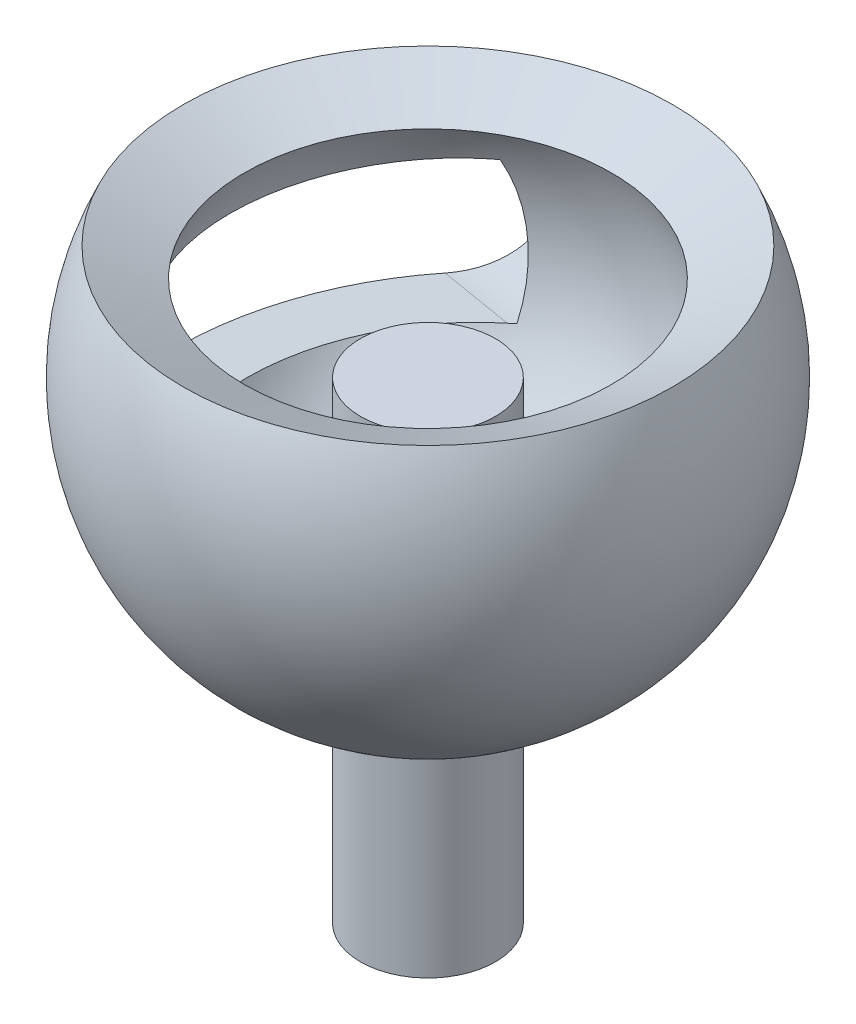
SolidWorks part; units mm, degrees
ref_plane "Plan de face" through (0, 0, 0) normal (0, 0, 1) x (1, 0, 0)
ref_plane "Plan de dessus" through (0, 0, 0) normal (0, 1, 0) x (1, 0, 0)
ref_plane "Plan de droite" through (0, 0, 0) normal (1, 0, 0) x (0, 0, -1)
sketch "Esquisse1" plane through (0, 0, 0) normal (0, 0, 1) x (1, 0, 0)
  line L0 (0, 0) -> (0, -12.9952) construction
  line L1 (0, 0) -> (0, -17.2806) construction
  line L2 (0, 0) -> (-10.8757, 5.0714) construction
  line L3 (-7.2505, 3.3809) -> (-5.4378, 2.5357)
  line L4 (0, 0) -> (10.4471, 0) construction
  line L5 (0, -6) -> (0, -8)
  arc A0 (-5.4378, 2.5357) -> (0, -6) centre (0, 0) ccw
  arc A1 (-7.2505, 3.3809) -> (0, -8) centre (0, 0) ccw
  dimension "D1" = 6
  dimension "D2" = 8
  dimension "D3" = 155
revolve "Révolution1" add sketch "Esquisse1" angle 360 about L0
sketch "Esquisse2" plane through (0, 0, 0) normal (0, 1, 0) x (1, 0, 0)
  circle A0 centre (0, 0) radius 2
  dimension "D1" = 4
extrude "Boss.-Extru.1" add sketch "Esquisse2" against normal blind 14
ref_plane "Plan1" through (-10.3936, -1.2992, -2.8186) normal (-0.9582, -0.1198, -0.2598) x (-0.2578, -0.0322, 0.9656)
sketch "Esquisse3" plane through (-10.3936, -1.2992, -2.8186) normal (-0.9582, -0.1198, -0.2598) x (-0.2578, -0.0322, 0.9656)
  line L0 (-4, 2) -> (4, 2)
  line L1 (-4, -2) -> (4, -2)
  arc A0 (4, 2) -> (4, -2) centre (4, 0) cw
  arc A1 (-4, 2) -> (-4, -2) centre (-4, 0) ccw
  dimension "D1" = 2
  dimension "D2" = 8
  dimension "D3" = 4
  dimension "D4" = 2
extrude "Enlèv. mat.-Extru.1" cut sketch "Esquisse3" against normal blind 7
